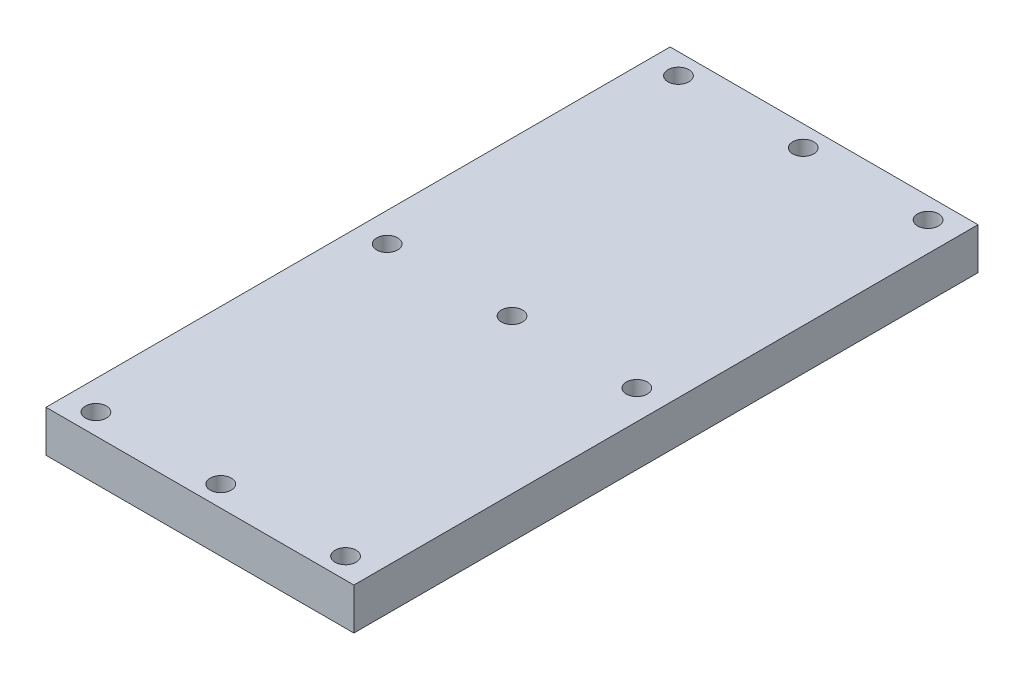
SolidWorks part; units mm, degrees
ref_plane "Plano frontal" through (0, 0, 0) normal (0, 0, 1) x (1, 0, 0)
ref_plane "Plano superior" through (0, 0, 0) normal (0, 1, 0) x (1, 0, 0)
ref_plane "Plano direito" through (0, 0, 0) normal (1, 0, 0) x (0, 0, -1)
sketch "Esboço1" plane through (0, 0, 0) normal (0, 1, 0) x (1, 0, 0)
  line L1 (0, 0) -> (37, 0)
  line L2 (0, 0) -> (0, 75)
  line L3 (0, 75) -> (37, 75)
  line L4 (37, 0) -> (37, 75)
  circle A0 centre (3.5, 72.5) radius 1.265
  circle A1 centre (18.5, 72.5) radius 1.265
  circle A2 centre (33.5, 72.5) radius 1.265
  circle A3 centre (18.5, 37.5) radius 1.265
  circle A4 centre (33.5, 37.5) radius 1.265
  circle A5 centre (18.5, 2.5) radius 1.265
  circle A6 centre (33.5, 2.5) radius 1.265
  circle A7 centre (3.5, 37.5) radius 1.265
  circle A8 centre (3.5, 2.5) radius 1.265
  dimension "D5" = 2.53
  dimension "D1" = 37
  dimension "D2" = 75
  dimension "D3" = 3.5
  dimension "D4" = 2.5
  dimension "D6" = 3
  dimension "D7" = 3
extrude "Ressalto-extrusão2" add sketch "Esboço1" along normal blind 5
